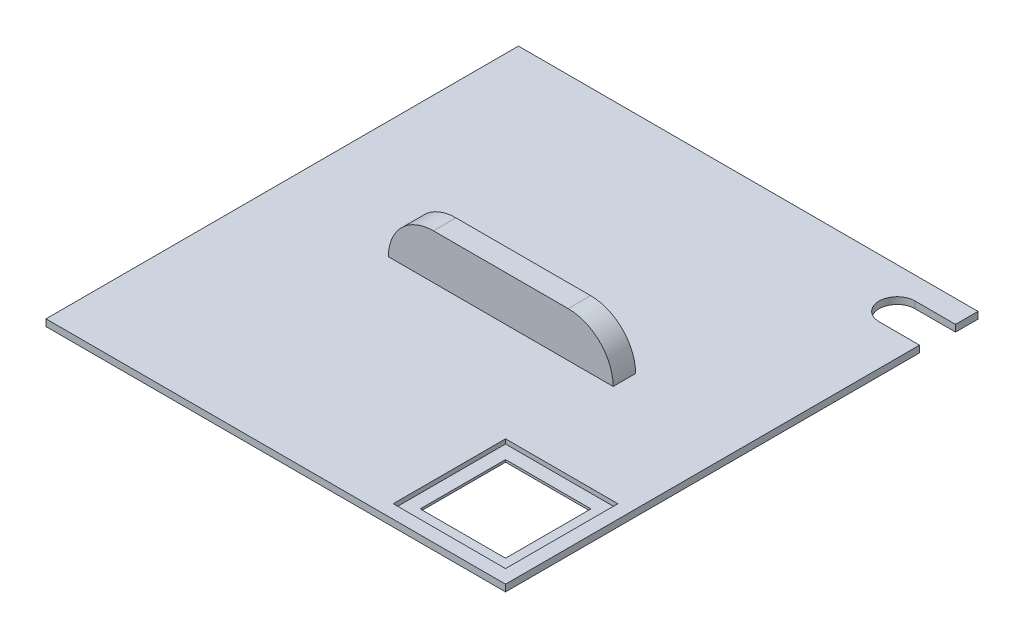
SolidWorks part; units mm, degrees
ref_plane "Front Plane" through (0, 0, 0) normal (0, 0, 1) x (1, 0, 0)
ref_plane "Top Plane" through (0, 0, 0) normal (0, 1, 0) x (1, 0, 0)
ref_plane "Right Plane" through (0, 0, 0) normal (1, 0, 0) x (0, 0, -1)
sketch "Sketch1" plane through (0, 0, 0) normal (0, 1, 0) x (1, 0, 0)
  line L0 (42.125, 47.5608) -> (51.125, 47.5608)
  line L1 (-51.125, 52.5608) -> (51.125, 52.5608)
  line L2 (-51.125, 52.5608) -> (-51.125, -52.5608)
  line L3 (-51.125, -52.5608) -> (51.125, -52.5608)
  line L4 (51.125, 52.5608) -> (51.125, -52.5608)
  line L9 (42.125, 39.5608) -> (51.125, 39.5608)
  arc A0 (42.125, 47.5608) -> (42.125, 39.5608) centre (42.125, 43.5608) ccw
  point P4 (0, 52.5608)
  point P6 (-51.125, 0)
  point P8 (42.125, 43.5608)
  point P10 (46.125, 43.5608)
  dimension "D3" = 8
  dimension "D2" = 9
  dimension "D4" = 9
  dimension "D5" = 105.1216
  dimension "D1" = 102.25
extrude "Boss-Extrude1" add sketch "Sketch1" along normal blind 1.5
sketch "Sketch2" plane through (0, 1.5, 0) normal (0, 1, 0) x (1, 0, 0)
  line L1 (-15, 2.5) -> (15, 2.5)
  line L2 (-15, 2.5) -> (-15, -2.5)
  line L3 (-15, -2.5) -> (15, -2.5)
  line L4 (15, 2.5) -> (15, -2.5)
  point P4 (0, 2.5)
  point P6 (15, 0)
  dimension "D1" = 30
  dimension "D2" = 5
extrude "Boss-Extrude2" add sketch "Sketch2" along normal blind 10
sketch "Sketch3" plane through (0, 1.5, 0) normal (0, 1, 0) x (1, 0, 0)
  line L0 (-15, -2.5) -> (-15, 2.5)
  line L3 (-15, 2.5) -> (-15, -2.5) construction
revolve "Revolve-Thin1" add sketch "Sketch3" angle 180 about L0 wall 10
mirror "Mirror1" about plane through (0, 0, 0) normal (1, 0, 0) of "Revolve-Thin1"
sketch "Sketch5" plane through (0, 1.5, 0) normal (0, 1, 0) x (1, 0, 0)
  line L0 (-51.125, -52.5608) -> (51.125, -52.5608) construction
  line L1 (48.125, -49.5608) -> (23.125, -49.5608)
  line L2 (48.125, -49.5608) -> (48.125, -24.5608)
  line L3 (48.125, -24.5608) -> (23.125, -24.5608)
  line L4 (23.125, -49.5608) -> (23.125, -24.5608)
  line L5 (35.625, -52.5608) -> (35.625, -49.5608)
  line L7 (48.125, -37.0608) -> (51.125, -37.0608)
  line L8 (51.125, 39.5608) -> (51.125, -52.5608) construction
  point P6 (35.625, -49.5608)
  dimension "D1" = 25
  dimension "D2" = 3
extrude "Cut-Extrude1" cut sketch "Sketch5" against normal blind 1 contours L4 L1 L2 L3
sketch "Sketch6" plane through (0, 0.5, 0) normal (0, 1, 0) x (1, 0, 0)
  line L5 (48.125, -49.5608) -> (48.125, -24.5608) construction
  line L8 (26.125, -27.5608) -> (45.125, -27.5608)
  line L14 (26.125, -27.5608) -> (26.125, -46.5608)
  line L15 (26.125, -46.5608) -> (45.125, -46.5608)
  line L16 (45.125, -27.5608) -> (45.125, -46.5608)
  line L17 (48.125, -24.5608) -> (23.125, -24.5608) construction
  line L18 (23.125, -49.5608) -> (23.125, -24.5608) construction
  dimension "D2" = 3
  dimension "D1" = 3
  dimension "D3" = 3
extrude "Cut-Extrude2" cut sketch "Sketch6" against normal blind 3 contours L16 L8 L14 L15
equation "\"D1@Boss-Extrude2\" = \"RoomSize\" * 0.1"
equation "\"D3@Revolve-Thin1\" = \"RoomSize\" * 0.1"
equation "\"CableSize\"= 8mm"
equation "\"D3@Sketch1\"=\"CableSize\""
equation "\"Windowsize\"= 25mm"
equation "\"WindowThick\"= 1mm"
equation "\"D1@Sketch5\"=\"Windowsize\""
equation "\"D1@Cut-Extrude1\"=\"WindowThick\""
equation "\"CoverThick\"= \"WallsThick\"/2"
equation "\"WindowHoldersize\"= 3mm"
equation "\"RoomSize\"= 100mm"
equation "\"RoomHeight\"= 5cm"
equation "\"WallsThick\"= 6mm"
equation "\"HoleWidth\"= 13mm"
equation "\"MeasureHoleSize\"= 3mm"
equation "\"ModelHeight\"= 1.7mm"
equation "\"HoleHeight\"= 3mm"
equation "\"D1@Sketch6\"=\"WindowHoldersize\""
equation "\"D2@Sketch6\"=\"WindowHoldersize\""
equation "\"D3@Sketch6\"=\"WindowHoldersize\""
equation "\"D2@Sketch5\"=\"WallsThick\"/2"
equation "\"D2@Sketch1\"=(3/2)*\"WallsThick\""
equation "\"D4@Sketch1\"=(3/2)*\"WallsThick\""
equation "\"D1@Sketch1\"=\"RoomSize\"+\"WallsThick\"/2-\"WallsThick\"/8"
